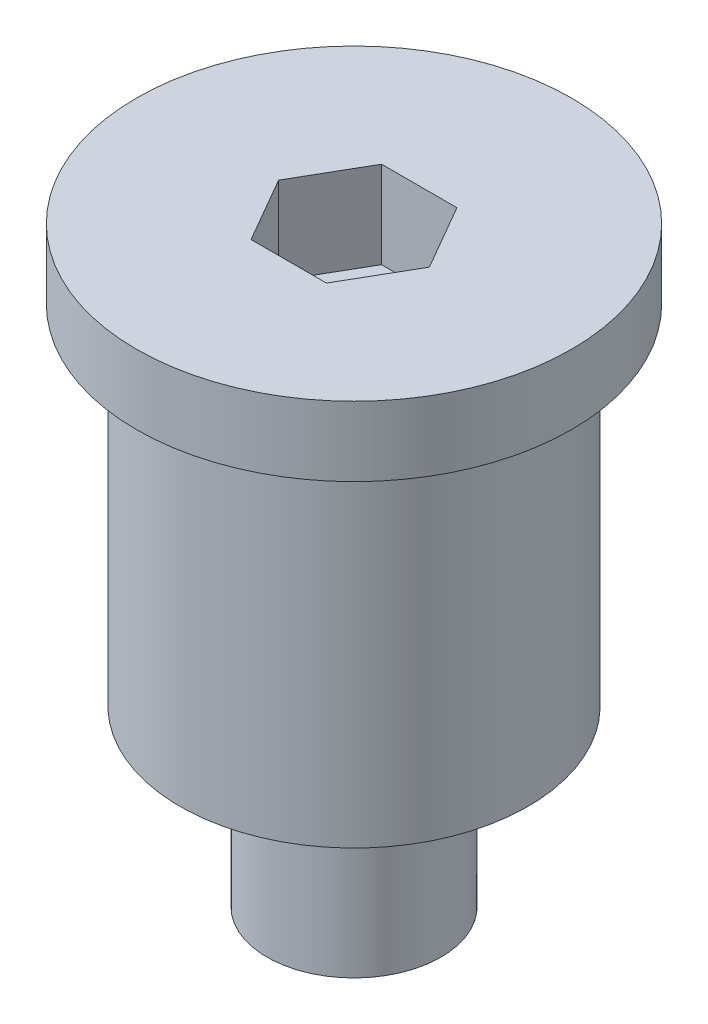
SolidWorks part; units mm, degrees
material "Plain Carbon Steel"
ref_plane "Front Plane" through (0, 0, 0) normal (0, 0, 1) x (1, 0, 0)
ref_plane "Top Plane" through (0, 0, 0) normal (0, 1, 0) x (1, 0, 0)
ref_plane "Right Plane" through (0, 0, 0) normal (1, 0, 0) x (0, 0, -1)
sketch "Sketch1" plane through (0, 0, 0) normal (1, 0, 0) x (0, 0, -1)
  line L0 (0, 0) -> (0, 21.59)
  line L1 (0, 21.59) -> (-7.9375, 21.59)
  line L2 (-7.9375, 21.59) -> (-7.9375, 19.05)
  line L3 (-7.9375, 19.05) -> (-6.35, 19.05)
  line L4 (-6.35, 19.05) -> (-6.35, 6.35)
  line L5 (-6.35, 6.35) -> (-3.175, 6.35)
  line L6 (-3.175, 6.35) -> (-3.175, 0)
  line L7 (-3.175, 0) -> (0, 0)
  dimension "D1" = 3.175
  dimension "D2" = 3.175
  dimension "D3" = 7.9375
  dimension "D4" = 12.7
  dimension "D5" = 2.54
  dimension "D6" = 6.35
revolve "Revolve1" add sketch "Sketch1" angle 360 about L0
sketch "Sketch2" plane through (0, 21.59, 0) normal (0, 1, 0) x (1, 0, 0)
  line L1 (-1.3748, 2.3813) -> (-2.7496, 0)
  line L2 (-2.7496, 0) -> (-1.3748, -2.3813)
  line L3 (-1.3748, -2.3813) -> (1.3748, -2.3812)
  line L4 (1.3748, -2.3812) -> (2.7496, 0)
  line L5 (2.7496, 0) -> (1.3748, 2.3813)
  line L6 (1.3748, 2.3813) -> (-1.3748, 2.3813)
  circle A0 centre (0, 0) radius 2.3813 construction
  dimension "D1" = 4.7625
extrude "Cut-Extrude1" cut sketch "Sketch2" against normal blind 3.175
